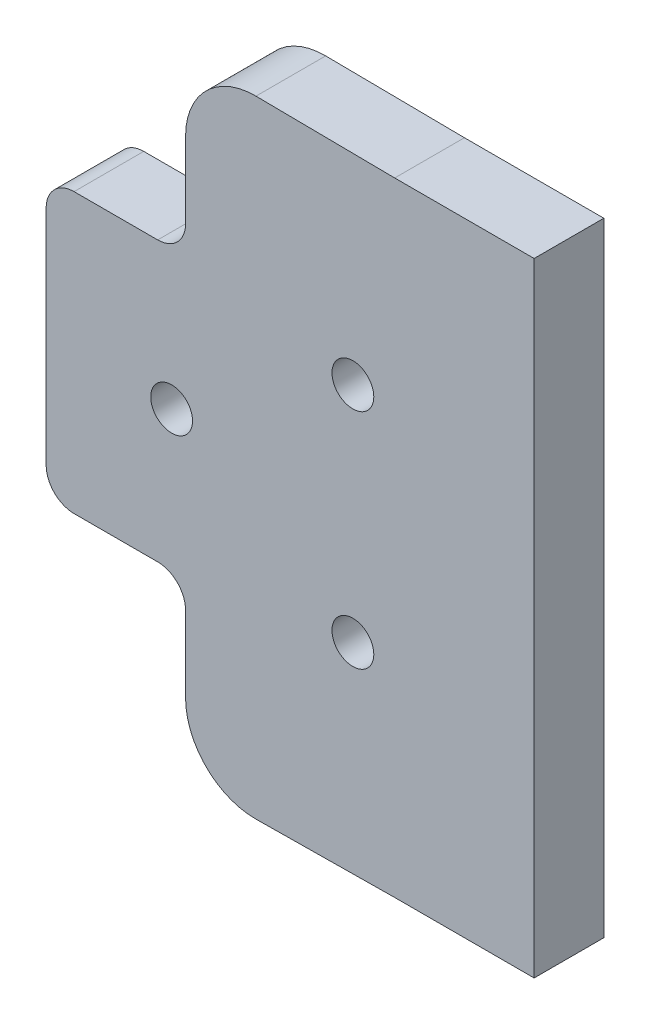
SolidWorks part; units mm, degrees
ref_plane "Front Plane" through (0, 0, 0) normal (0, 0, 1) x (1, 0, 0)
ref_plane "Top Plane" through (0, 0, 0) normal (0, 1, 0) x (1, 0, 0)
ref_plane "Right Plane" through (0, 0, 0) normal (1, 0, 0) x (0, 0, -1)
sketch "Sketch1" plane through (0, 0, 0) normal (0, 0, 1) x (1, 0, 0)
  line L12 (1.0833, 19.8763) -> (1.0833, 14.4203)
  line L17 (-0.9167, 12.4203) -> (-6.9167, 12.4203)
  line L18 (-8.9167, 10.4203) -> (-8.9167, -5.5797)
  line L19 (-6.9167, -7.5797) -> (-0.9167, -7.5797)
  line L20 (1.0833, -9.5797) -> (1.0833, -15.0358)
  line L23 (16.0833, 24.7682) -> (26.0833, 24.7682)
  line L25 (16.0833, -19.9276) -> (26.0833, -19.9276)
  line L26 (26.0833, 24.7682) -> (26.0833, -19.9276)
  arc A18 (6.1318, 24.8761) -> (1.0833, 19.8763) centre (6.0833, 19.8763) ccw
  arc A19 (-0.9167, 12.4203) -> (1.0833, 14.4203) centre (-0.9167, 14.4203) ccw
  arc A20 (-6.9167, 12.4203) -> (-8.9167, 10.4203) centre (-6.9167, 10.4203) ccw
  arc A21 (-8.9167, -5.5797) -> (-6.9167, -7.5797) centre (-6.9167, -5.5797) ccw
  arc A22 (1.0833, -9.5797) -> (-0.9167, -7.5797) centre (-0.9167, -9.5797) ccw
  arc A23 (1.0833, -15.0358) -> (6.1318, -20.0355) centre (6.0833, -15.0358) ccw
  circle A24 centre (13.0833, 10.4203) radius 1.5
  circle A25 centre (13.0833, 10.4203) radius 2.15
  circle A26 centre (0.0833, 2.4203) radius 1.5
  circle A27 centre (0.0833, 2.4203) radius 2.15
  circle A28 centre (13.0833, -5.5797) radius 2.15
  circle A29 centre (13.0833, -5.5797) radius 1.5
  spline S0 degree 3 poles (16.0833, 24.7682) (12.5708, 24.8091) (9.2481, 24.8459) (6.1318, 24.8761) knots 0.046328 0.046328 0.046328 0.046328 0.128883 0.128883 0.128883 0.128883
  spline S1 degree 3 poles (6.1318, -20.0355) (9.2481, -20.0053) (12.5708, -19.9686) (16.0833, -19.9276) knots 0.046328 0.046328 0.046328 0.046328 0.128883 0.128883 0.128883 0.128883
  dimension "D2" = 3
  dimension "D1" = 10
extrude "Boss-Extrude1" add sketch "Sketch1" along normal mid plane 5
